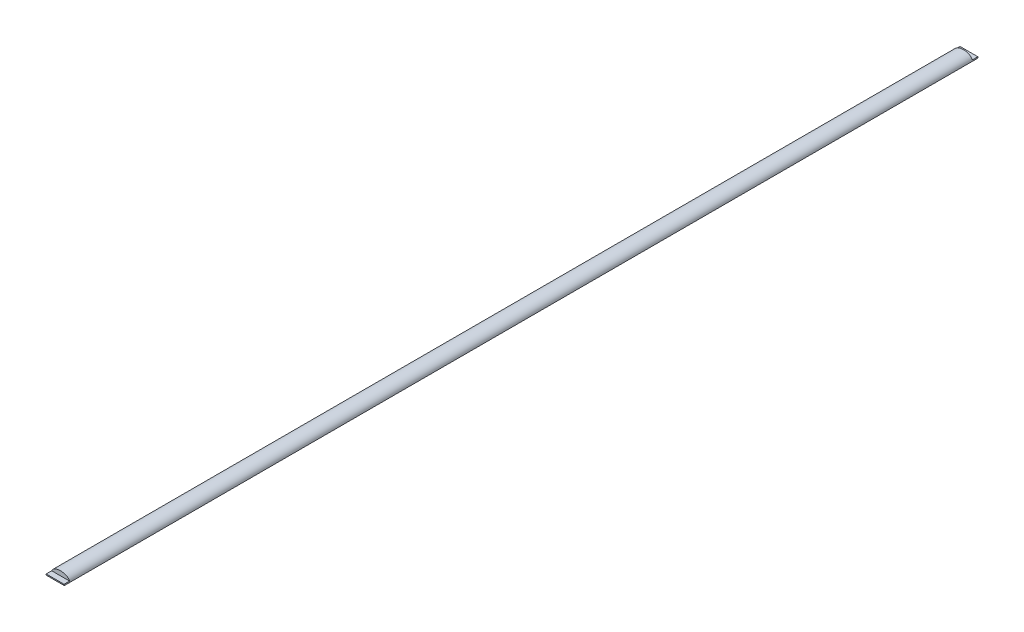
SolidWorks part; units mm, degrees
ref_plane "Front Plane" through (0, 0, 0) normal (0, 0, 1) x (1, 0, 0)
ref_plane "Top Plane" through (0, 0, 0) normal (0, 1, 0) x (1, 0, 0)
ref_plane "Right Plane" through (0, 0, 0) normal (1, 0, 0) x (0, 0, -1)
sketch "Sketch1" plane through (0, 0, 0) normal (0, 0, 1) x (1, 0, 0)
  line L0 (-5, 0) -> (5, 0)
  ellipse E0 centre (0, 0) end of major axis (-5, 0) minor radius 3 (5, 0) -> (-5, 0) ccw
  point P4 (0, 0)
  dimension "D1" = 10
  dimension "D2" = 3
extrude "Boss-Extrude1" add sketch "Sketch1" along normal mid plane 500
sketch "Sketch2" plane through (0, 0, 250) normal (0, 0, 1) x (1, 0, 0)
  line L0 (4.899, 0.6) -> (-4.899, 0.6)
  line L1 (-5, 0) -> (5, 0)
  line L2 (-5, 0) -> (5, 0)
  ellipse E1 centre (0, 0) end of major axis (-5, 0) minor radius 3 (5, 0) -> (-5, 0) ccw
  ellipse E2 centre (0, 0) end of major axis (-5, 0) minor radius 3 (5, 0) -> (-5, 0) ccw
  ellipse M4 centre (0, 0) end of major axis (-5, 0) minor radius 3 (5, 0) -> (-5, 0) ccw
  dimension "D2" = 0.6
  dimension "D1" = 0
extrude "Cut-Extrude1" cut sketch "Sketch2" against normal blind 3 contours L0 M4
mirror "Mirror1" about plane through (0, 0, 0) normal (0, 0, 1) of "Cut-Extrude1"
